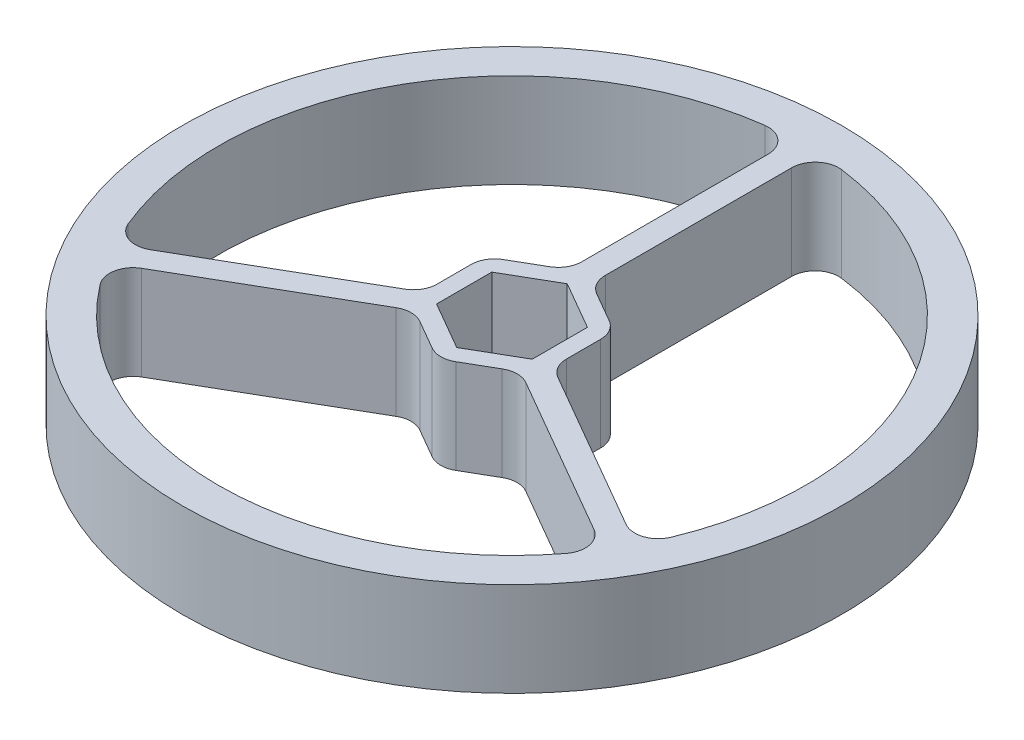
SolidWorks part; units mm, degrees
material "PET"
ref_plane "Front Plane" through (0, 0, 0) normal (0, 0, 1) x (1, 0, 0)
ref_plane "Top Plane" through (0, 0, 0) normal (0, 1, 0) x (1, 0, 0)
ref_plane "Right Plane" through (0, 0, 0) normal (1, 0, 0) x (0, 0, -1)
sketch "Sketch1" plane through (0, 0, 0) normal (0, 1, 0) x (1, 0, 0)
  line L0 (0, 0) -> (0, 39.624) construction
  line L1 (-1.5875, 0) -> (-1.5875, 39.624)
  line L2 (1.5875, 0) -> (1.5875, 39.624)
  line L3 (0, 0) -> (-34.3154, -19.812) construction
  line L4 (0.7938, -1.3748) -> (-33.5216, -21.1868)
  line L5 (-0.7938, 1.3748) -> (-35.1091, -18.4372)
  line L6 (0, 0) -> (34.3154, -19.812) construction
  line L7 (0.7938, 1.3748) -> (35.1091, -18.4372)
  line L8 (-0.7938, -1.3748) -> (33.5216, -21.1868)
  line L10 (-6.4516, 3.7248) -> (-6.4516, -3.7248)
  line L11 (-6.4516, -3.7248) -> (0, -7.4497)
  line L12 (0, -7.4497) -> (6.4516, -3.7248)
  line L13 (6.4516, -3.7248) -> (6.4516, 3.7248)
  line L14 (6.4516, 3.7248) -> (0, 7.4497)
  line L15 (0, 7.4497) -> (-6.4516, 3.7248)
  line L16 (-8.7376, 5.0447) -> (-8.7376, -5.0447)
  line L17 (-8.7376, -5.0447) -> (0, -10.0893)
  line L18 (0, -10.0893) -> (8.7376, -5.0447)
  line L19 (8.7376, -5.0447) -> (8.7376, 5.0447)
  line L20 (8.7376, 5.0447) -> (0, 10.0893)
  line L21 (0, 10.0893) -> (-8.7376, 5.0447)
  circle A0 centre (0, 0) radius 44.45
  circle A1 centre (0, 0) radius 39.624
  arc A4 (-1.5875, 0) -> (1.5875, 0) centre (0, 0) ccw
  arc A5 (1.5875, 39.624) -> (-1.5875, 39.624) centre (0, 39.624) ccw
  arc A6 (0.7938, -1.3748) -> (-0.7938, 1.3748) centre (0, 0) ccw
  arc A7 (-35.1091, -18.4372) -> (-33.5216, -21.1868) centre (-34.3154, -19.812) ccw
  arc A8 (0.7938, 1.3748) -> (-0.7938, -1.3748) centre (0, 0) ccw
  arc A9 (33.5216, -21.1868) -> (35.1091, -18.4372) centre (34.3154, -19.812) ccw
  circle A10 centre (0, 0) radius 6.4516 construction
  circle A11 centre (0, 0) radius 8.7376 construction
  point P7 (0, 19.812)
  point P14 (-17.1577, -9.906)
  point P21 (17.1577, -9.906)
  dimension "D1" = 88.9
  dimension "D2" = 4.826
  dimension "D3" = 12.9032
  dimension "D4" = 2.286
  dimension "D5" = 1.5875
  dimension "D6" = 120
extrude "Boss-Extrude1" add sketch "Sketch1" along normal blind 12.7
fillet "Fillet1" radius 3.175 15 edges at (1.5875, 6.35, -39.5922) (-1.5875, 6.35, -39.5922) (-35.0816, 6.35, 18.4213) (35.0816, 6.35, 18.4213) (33.4941, 6.35, 21.1709) (-33.4941, 6.35, 21.1709) (-8.7376, 6.35, 3.2116) (-8.7376, 6.35, -5.0447) (-1.5875, 6.35, -9.1728) (1.5875, 6.35, -9.1728) (8.7376, 6.35, -5.0447) (8.7376, 6.35, 3.2116) (7.1501, 6.35, 5.9612) (0, 6.35, 10.0893) (-7.1501, 6.35, 5.9612)
